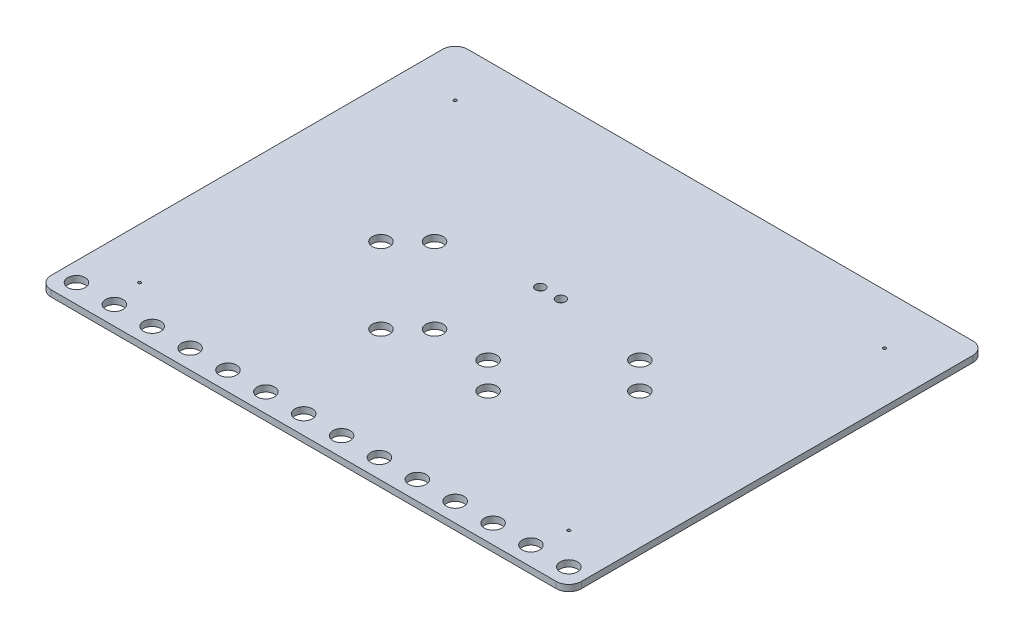
SolidWorks part; units mm, degrees
material "Acrylic (Medium-high impact)"
ref_plane "Front Plane" through (0, 0, 0) normal (0, 0, 1) x (1, 0, 0)
ref_plane "Top Plane" through (0, 0, 0) normal (0, 1, 0) x (1, 0, 0)
ref_plane "Right Plane" through (0, 0, 0) normal (1, 0, 0) x (0, 0, -1)
sketch "Sketch1" plane through (0, 0, 0) normal (0, 1, 0) x (1, 0, 0)
  line L1 (-266.7, -209.55) -> (266.7, -209.55)
  line L2 (-266.7, -209.55) -> (-266.7, 209.55)
  line L3 (-266.7, 209.55) -> (266.7, 209.55)
  line L4 (266.7, -209.55) -> (266.7, 209.55)
  line L5 (-266.7, -209.55) -> (266.7, 209.55) construction
  line L6 (-266.7, 209.55) -> (266.7, -209.55) construction
  point P0 (0, 0)
  dimension "D1" = 419.1
  dimension "D2" = 533.4
extrude "Boss-Extrude1" add sketch "Sketch1" along normal mid plane 6.35
sketch "Sketch2" plane through (0, 3.175, 0) normal (0, 1, 0) x (1, 0, 0)
  line L0 (-266.7, -209.55) -> (266.7, -209.55) construction
  line L4 (-266.7, 209.55) -> (-266.7, -209.55) construction
  circle A0 centre (-209.55, -190.5) radius 4.4196
  circle A1 centre (-171.45, -190.5) radius 4.4196
  circle A2 centre (-133.35, -190.5) radius 4.4196
  circle A3 centre (-95.25, -190.5) radius 4.4196
  circle A4 centre (-57.15, -190.5) radius 4.4196
  circle A5 centre (-19.05, -190.5) radius 4.4196
  circle A6 centre (19.05, -190.5) radius 4.4196
  circle A7 centre (-247.65, -190.5) radius 4.4196
  circle A8 centre (57.15, -190.5) radius 4.4196
  circle A9 centre (95.25, -190.5) radius 4.4196
  circle A10 centre (133.35, -190.5) radius 4.4196
  circle A11 centre (171.45, -190.5) radius 4.4196
  circle A12 centre (209.55, -190.5) radius 4.4196
  circle A13 centre (247.65, -190.5) radius 4.4196
  circle A14 centre (285.75, -190.5) radius 4.4196
  dimension "D1" = 8.8392
  dimension "D6" = 19.05
  dimension "D4" = 38.1
  dimension "D2" = 15
  dimension "D3" = 19.05
extrude "Cut-Extrude1" cut sketch "Sketch2" against normal through all
sketch "Sketch3" plane through (0, 3.175, 0) normal (0, 1, 0) x (1, 0, 0)
  line L0 (-247.65, -190.5) -> (-209.55, -190.5) construction
  circle A0 centre (-247.65, -190.5) radius 8.7312
  circle A1 centre (-209.55, -190.5) radius 8.7312
  circle A2 centre (-171.45, -190.5) radius 8.7312
  circle A3 centre (-133.35, -190.5) radius 8.7312
  circle A4 centre (-95.25, -190.5) radius 8.7313
  circle A5 centre (-57.15, -190.5) radius 8.7313
  circle A6 centre (-19.05, -190.5) radius 8.7313
  circle A7 centre (19.05, -190.5) radius 8.7313
  circle A8 centre (57.15, -190.5) radius 8.7312
  circle A9 centre (95.25, -190.5) radius 8.7313
  circle A10 centre (133.35, -190.5) radius 8.7313
  circle A11 centre (171.45, -190.5) radius 8.7313
  circle A12 centre (209.55, -190.5) radius 8.7313
  circle A13 centre (247.65, -190.5) radius 8.7313
  circle A14 centre (285.75, -190.5) radius 8.7313
  circle A16 centre (323.85, -190.5) radius 8.7313 [skipped]
  dimension "D1" = 17.4625
  dimension "D2" = 16
  dimension "D3" = 38.1
extrude "Cut-Extrude2" cut sketch "Sketch3" against normal through all
fillet "Fillet1" radius 12.7 4 edges at (266.7, 0, 209.55) (266.7, 0, -209.55) (-266.7, 0, -209.55) (-266.7, 0, 209.55)
sketch "Sketch4" [suppressed] plane through (0, 3.175, 0) normal (0, 1, 0) x (1, 0, 0)
  line L0 (-254, -209.55) -> (254, -209.55) construction
  line L1 (0, -158.75) -> (157.1545, -1.5955) construction
  line L2 (0, -158.75) -> (-157.1545, -1.5955) construction
  line L3 (-157.1545, -1.5955) -> (0, 155.559) construction
  line L4 (157.1545, -1.5955) -> (0, 155.559) construction
  line L5 (0, -158.75) -> (0, 155.559) construction
  line L6 (-157.1545, -1.5955) -> (157.1545, -1.5955) construction
  line L7 (-71.842, 38.8156) -> (71.842, 38.8156) construction
  line L8 (157.1545, -1.5955) -> (53.8815, -104.8685) construction
  line L9 (157.1545, -1.5955) -> (103.2729, 52.286) construction
  line L10 (53.8815, -104.8685) -> (0, -50.9869) construction
  line L11 (103.2729, 52.286) -> (0, -50.9869) construction
  line L12 (-157.1545, -1.5955) -> (-103.2729, 52.286) construction
  line L13 (-157.1545, -1.5955) -> (-53.8815, -104.8685) construction
  line L14 (-103.2729, 52.286) -> (0, -50.9869) construction
  line L15 (-53.8815, -104.8685) -> (0, -50.9869) construction
  line L16 (-130.2137, -1.5955) -> (-103.2729, 25.3453) construction
  line L17 (-130.2137, -1.5955) -> (-53.8815, -77.9277) construction
  line L18 (-103.2729, 25.3453) -> (-26.9408, -50.9869) construction
  line L19 (-53.8815, -77.9277) -> (-26.9408, -50.9869) construction
  line L20 (26.9408, -50.9869) -> (53.8815, -77.9277) construction
  line L21 (26.9408, -50.9869) -> (103.2729, 25.3453) construction
  line L22 (53.8815, -77.9277) -> (130.2137, -1.5955) construction
  line L23 (103.2729, 25.3453) -> (130.2137, -1.5955) construction
  line L24 (-71.842, 38.8156) -> (0, 110.6577) construction
  line L25 (-71.842, 38.8156) -> (0, -33.0264) construction
  line L26 (0, 110.6577) -> (71.842, 38.8156) construction
  line L27 (0, -33.0264) -> (71.842, 38.8156) construction
  line L32 (-254, -209.55) -> (254, -209.55) construction
  circle A0 centre (-103.2729, 25.3453) radius 4.4196
  circle A1 centre (-130.2137, -1.5955) radius 4.4196
  circle A2 centre (-53.8815, -77.9277) radius 4.4196
  circle A3 centre (-26.9408, -50.9869) radius 4.4196
  circle A4 centre (26.9408, -50.9869) radius 4.4196
  circle A5 centre (53.8815, -77.9277) radius 4.4196
  circle A6 centre (130.2137, -1.5955) radius 4.4196
  circle A7 centre (103.2729, 25.3453) radius 4.4196
  circle A8 centre (0, 38.8156) radius 6.477
  circle A9 centre (-10.3187, 38.8156) radius 2.2035
  circle A10 centre (10.3188, 38.8156) radius 2.2034
  point P0 (0, -1.5955)
  point P13 (0, 38.8156)
  dimension "D9" = 8.8392
  dimension "D12" = 12.954
  dimension "D13" = 4.4069
  dimension "D15" = 4.4069
  dimension "D1" = 45
  dimension "D2" = 222.25
  dimension "D3" = 146.05
  dimension "D4" = 76.2
  dimension "D5" = 19.05
  dimension "D6" = 19.05
  dimension "D7" = 19.05
  dimension "D8" = 19.05
  dimension "D10" = 101.6
  dimension "D11" = 12.7
  dimension "D14" = 50.8
  dimension "D16" = 10.3187
  dimension "D17" = 10.3187
  dimension "D18" = 248.3656
extrude "Cut-Extrude3" [suppressed] cut sketch "Sketch4" against normal through all
sketch "Sketch5" plane through (0, 3.175, 0) normal (0, 1, 0) x (1, 0, 0)
  line L1 (-215.9, -158.75) -> (215.9, -158.75) construction
  line L2 (-215.9, -158.75) -> (-215.9, 158.75) construction
  line L3 (-215.9, 158.75) -> (215.9, 158.75) construction
  line L4 (215.9, -158.75) -> (215.9, 158.75) construction
  line L5 (-215.9, -158.75) -> (215.9, 158.75) construction
  line L6 (-215.9, 158.75) -> (215.9, -158.75) construction
  line L7 (-254, -209.55) -> (254, -209.55) construction
  line L8 (266.7, -196.85) -> (266.7, 196.85) construction
  circle A0 centre (-215.9, 158.75) radius 1.5367
  circle A1 centre (215.9, 158.75) radius 1.5367
  circle A2 centre (215.9, -158.75) radius 1.5367
  circle A3 centre (-215.9, -158.75) radius 1.5367
  point P0 (0, 0)
  dimension "D3" = 3.0734
  dimension "D1" = 50.8
  dimension "D2" = 50.8
extrude "Cut-Extrude4" cut sketch "Sketch5" against normal through all
sketch "Sketch6" plane through (0, 3.175, 0) normal (0, 1, 0) x (1, 0, 0)
  line L0 (-10.3187, 38.8156) -> (10.3187, 38.8156) construction
  line L1 (-254, -209.55) -> (254, -209.55) construction
  circle A0 centre (-10.3187, 38.8156) radius 4.7625
  circle A1 centre (10.3187, 38.8156) radius 4.7625
  point P4 (0, 38.8156)
  dimension "D2" = 9.525
  dimension "D1" = 20.6375
  dimension "D3" = 248.3656
extrude "Cut-Extrude5" cut sketch "Sketch6" against normal through all
sketch "Sketch7" plane through (0, 3.175, 0) normal (0, 1, 0) x (1, 0, 0)
  line L1 (0, -158.75) -> (157.1545, -1.5955) construction
  line L2 (0, -158.75) -> (-157.1545, -1.5955) construction
  line L3 (-157.1545, -1.5955) -> (0, 155.559) construction
  line L4 (157.1545, -1.5955) -> (0, 155.559) construction
  line L5 (0, -158.75) -> (0, 155.559) construction
  line L6 (-157.1545, -1.5955) -> (157.1545, -1.5955) construction
  line L8 (157.1545, -1.5955) -> (53.8815, -104.8685) construction
  line L9 (157.1545, -1.5955) -> (103.2729, 52.286) construction
  line L10 (53.8815, -104.8685) -> (0, -50.9869) construction
  line L11 (103.2729, 52.286) -> (0, -50.9869) construction
  line L12 (-157.1545, -1.5955) -> (-103.2729, 52.286) construction
  line L13 (-157.1545, -1.5955) -> (-53.8815, -104.8685) construction
  line L14 (-103.2729, 52.286) -> (0, -50.9869) construction
  line L15 (-53.8815, -104.8685) -> (0, -50.9869) construction
  line L16 (-130.2137, -1.5955) -> (-103.2729, 25.3453) construction
  line L17 (-130.2137, -1.5955) -> (-53.8815, -77.9277) construction
  line L18 (-103.2729, 25.3453) -> (-26.9408, -50.9869) construction
  line L19 (-53.8815, -77.9277) -> (-26.9408, -50.9869) construction
  line L20 (26.9408, -50.9869) -> (53.8815, -77.9277) construction
  line L21 (26.9408, -50.9869) -> (103.2729, 25.3453) construction
  line L22 (53.8815, -77.9277) -> (130.2137, -1.5955) construction
  line L23 (103.2729, 25.3453) -> (130.2137, -1.5955) construction
  line L24 (-254, -209.55) -> (254, -209.55) construction
  circle A0 centre (-103.2729, 25.3453) radius 8.7312
  circle A1 centre (-130.2137, -1.5955) radius 8.7312
  circle A2 centre (-53.8815, -77.9277) radius 8.7312
  circle A3 centre (-26.9408, -50.9869) radius 8.7312
  circle A4 centre (26.9408, -50.9869) radius 8.7312
  circle A5 centre (53.8815, -77.9277) radius 8.7312
  circle A6 centre (130.2137, -1.5955) radius 8.7312
  circle A7 centre (103.2729, 25.3453) radius 8.7312
  point P0 (0, -1.5955)
  dimension "D9" = 17.4625
  dimension "D1" = 50.8
  dimension "D2" = 222.25
  dimension "D3" = 146.05
  dimension "D4" = 76.2
  dimension "D5" = 19.05
  dimension "D6" = 19.05
  dimension "D7" = 19.05
  dimension "D8" = 19.05
extrude "Cut-Extrude6" cut sketch "Sketch7" against normal through all
equation "\"D2@Sketch5\"=\"D1@Sketch5\""
